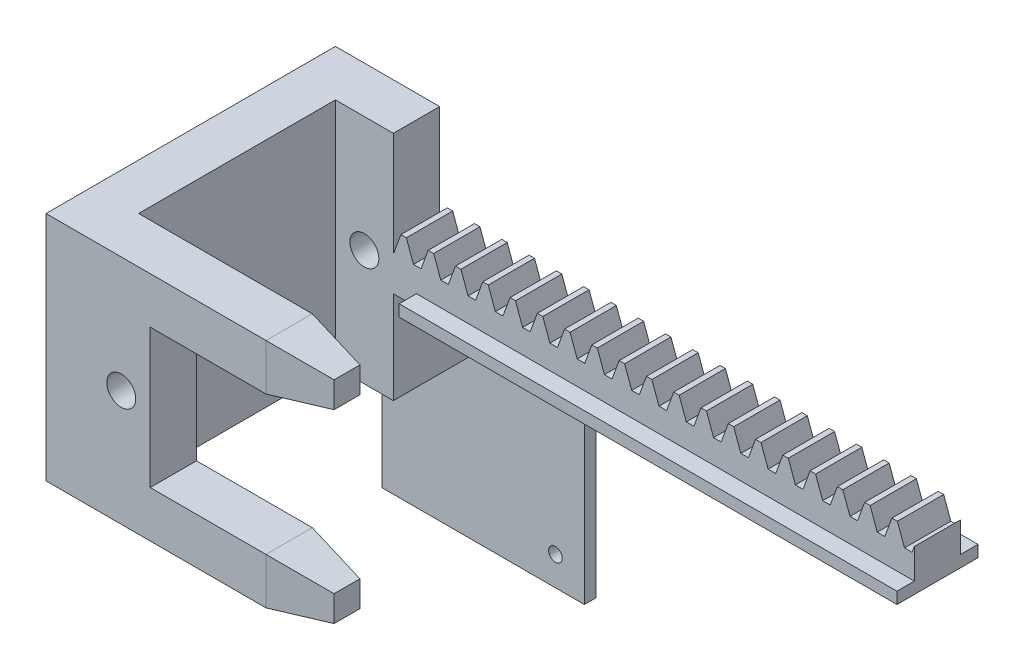
SolidWorks part; units mm, degrees
extrude "Blank" add sketch "BlankSke" against normal blind 8
sketch "BlankSke" plane through (0, 0, 0) normal (0, 0, 1) x (1, 0, 0)
  line L1 (0, 0) -> (100, 0)
  line L2 (0, 0) -> (0, 9.5)
  line L3 (0, 9.5) -> (100, 9.5)
  line L4 (100, 0) -> (100, 9.5)
  dimension "Length" = 100
  dimension "Blank_height" = 9.5
material "ABS PC"
ref_plane "Plane1" through (0, 0, 0) normal (0, 0, 1) x (1, 0, 0)
ref_plane "Plane2" through (0, 0, 0) normal (0, 1, 0) x (1, 0, 0)
ref_plane "Plane3" through (0, 0, 0) normal (1, 0, 0) x (0, 0, -1)
sketch "HoldingSke" plane through (0, 0, 0) normal (0, 1, 0) x (1, 0, 0)
  line L0 (0, 0) -> (0.0928, 0.6602)
  line L1 (-15, 0) -> (100, 0) construction
  line L2 (0, 0) -> (-2.1039, 2.3779)
  line L3 (0, 0) -> (-11.863, 4.5341)
  line L4 (0, 0) -> (7.9495, 3.3743)
  line L5 (0, 0) -> (-23.7986, -8.8762)
  line L6 (0, 0) -> (-10.5278, -7.1032)
  line L9 (-71.009, 38.7566) -> (22.9603, 72.9586)
  line L10 (-76.2, 3.8779) -> (-68.2, 3.8779)
  line L11 (0, 0) -> (-8, 0)
  line L12 (-76.2, 101.6) -> (-76.147, 101.6)
  line L13 (24.9733, 27.94) -> (52.9518, 28.4284)
  line L14 (24.9733, 27.94) -> (24.9743, 27.94)
  line L15 (24.9733, 27.94) -> (100.4006, 29.5858)
  circle A0 centre (0, 0) radius 19.05
  circle A1 centre (0, 0) radius 4
  circle A2 centre (0, 0) radius 12.7
  dimension "MPH" = 8
  dimension "Diameter" = 38.1
  dimension "Num_teeth" = 23
  dimension "Pitch" = 0.6667
  dimension "Show_teeth" = 998
  dimension "Thickness" = 12.7
  dimension "Ap" = 20
  dimension "Pitch_height" = 8
  dimension "Width" = 8
  dimension "Backlash" = 0.053
  dimension "Addendum_fac" = 1
  dimension "Dedendum_fac" = 1.25
  dimension "Clearance_fac" = 0.25
  dimension "Dedendum_add" = 0.001
  dimension "Length" = 100
  dimension "Module" = 1.5
sketch "TooCutSkeIll" plane through (0, 0, 0) normal (0, 0, 1) x (1, 0, 0)
  line L0 (-1.8687, 9.4605) -> (-0.7447, 6.3724)
  line L1 (-0.3914, 6.125) -> (0.3914, 6.125)
  line L2 (0.7447, 6.3724) -> (1.8687, 9.4605)
  line L3 (100, 9.5) -> (0, 9.5) construction
  line L4 (0, 0) -> (0, 64.897) construction
  line L5 (-13.208, 8) -> (12.954, 8) construction
  line L6 (0, 0) -> (100, 0) construction
  line L7 (1.3371, 8) -> (1.3371, 48.7463) construction
  line L8 (-1.3371, 8) -> (-1.3371, 48.7463) construction
  line L9 (1.9251, 9.5) -> (1.9251, 9.5254)
  line L10 (-1.9251, 9.5) -> (-1.9251, 9.5254)
  line L11 (-1.9251, 9.5254) -> (1.9251, 9.5254)
  arc A0 (0.3914, 6.125) -> (0.7447, 6.3724) centre (0.3914, 6.501) ccw
  arc A1 (-0.7447, 6.3724) -> (-0.3914, 6.125) centre (-0.3914, 6.501) ccw
  arc A2 (1.9251, 9.5) -> (1.8687, 9.4605) centre (1.9251, 9.44) ccw
  arc A3 (-1.8687, 9.4605) -> (-1.9251, 9.5) centre (-1.9251, 9.44) ccw
  dimension "Pitch_height" = 8
  dimension "Addendum_plus" = 1.5254
  dimension "Pressure_angle" = 20
  dimension "Gap_width" = 2.6742
  dimension "Dedendum" = 1.875
extrude "ToothCutIll" [suppressed] cut sketch "TooCutSkeIll" against normal through all
sketch "TooCutSkeSim" plane through (0, 0, 0) normal (0, 0, 1) x (1, 0, 0)
  line L0 (0.6547, 6.125) -> (-0.6547, 6.125)
  line L1 (1.8923, 9.5254) -> (0.6547, 6.125)
  line L2 (0, 17.4625) -> (0, 53.467) construction
  line L3 (1.8923, 9.5254) -> (-1.8923, 9.5254)
  line L6 (-1.8923, 9.5254) -> (-0.6547, 6.125)
  line L9 (-1.3371, 8) -> (1.3371, 8) construction
  line L10 (0, 0) -> (100, 0) construction
  line L11 (1.3371, 8) -> (1.3371, 53.467) construction
  line L12 (-1.3371, 8) -> (-1.3371, 53.467) construction
  dimension "Pitch_height" = 8
  dimension "Addendum_plus" = 1.5254
  dimension "Pressure_angle" = 20
  dimension "Gap_width" = 2.6742
  dimension "Dedendum" = 1.875
extrude "ToothCutSim" cut sketch "TooCutSkeSim" against normal through all
pattern_linear "TeethCuts" count 22 spacing 4.7124 along (1, 0, 0) of "ToothCutIll", "ToothCutSim"
sketch "Sketch1" plane through (0, 0, 0) normal (-1, 0, 0) x (0, 0, 1)
  line L0 (0, 0) -> (3, 0)
  line L1 (3, 0) -> (3, 2)
  line L2 (3, 2) -> (0, 2)
  line L3 (0, 6.125) -> (0, 0) construction
  line L4 (0, 2) -> (0, 0)
  dimension "D1" = 3
  dimension "D2" = 2
extrude "Boss-Extrude1" add sketch "Sketch1" against normal blind 100
ref_plane "Plane4" through (0, 0, -4) normal (0, 0, -1) x (-1, 0, 0)
mirror "Mirror1" about plane through (0, 0, -4) normal (0, 0, -1) of "Boss-Extrude1"
sketch "Sketch2" plane through (0, 0, 0) normal (0, -1, 0) x (-1, 0, 0)
  line L0 (0, 0) -> (-100, 0) construction
  line L1 (0, 11) -> (0, -3) construction
  line L2 (-100, 11) -> (-100, -3) construction
  line L3 (-100, -3) -> (0, -3) construction
  dimension "D1" = 3
sketch "Sketch4" plane through (0, 0, 0) normal (-1, 0, 0) x (0, 0, 1)
  line L0 (-8, -16) -> (-8, 24)
  line L1 (-8, 24) -> (42, 24)
  line L2 (42, 24) -> (42, -16)
  line L3 (42, -16) -> (-8, -16)
  line L4 (-11, 0) -> (3, 0) construction
  dimension "D1" = 40
  dimension "D2" = 50
  dimension "D3" = 24
extrude "Boss-Extrude2" add sketch "Sketch4" along normal blind 8
sketch "Sketch5" plane through (0, 0, 0) normal (1, 0, 0) x (0, 0, -1)
  line L0 (-42, 24) -> (-34, 24)
  line L1 (-42, 24) -> (8, 24) construction
  line L2 (-34, 24) -> (-34, 16)
  line L3 (-34, 16) -> (-42, 16)
  line L4 (-42, -16) -> (-42, 24) construction
  line L5 (-42, 16) -> (-42, 24)
  dimension "D1" = 8
  dimension "D2" = 8
extrude "Boss-Extrude3" add sketch "Sketch5" along normal blind 30
ref_plane "Plane5" through (0, 4, 0) normal (0, 1, 0) x (1, 0, 0)
mirror "Mirror2" about plane through (0, 4, 0) normal (0, 1, 0) of "Boss-Extrude3"
sketch "Sketch6" plane through (30, 0, 0) normal (1, 0, 0) x (0, 0, -1)
  line L0 (-42, 16) -> (-42, 24)
  line L1 (-42, 24) -> (-34, 24)
  line L2 (-34, 24) -> (-42, 24) construction
  line L3 (-34, 16) -> (-34, 24) construction
  line L4 (-34, 24) -> (-34, 16)
  line L5 (-42, 16) -> (-34, 16) construction
  line L6 (-34, 16) -> (-42, 16)
extrude "Boss-Extrude4" add sketch "Sketch6" along normal blind 10 draft 10
mirror "Mirror3" about plane through (0, 4, 0) normal (0, 1, 0) of "Boss-Extrude4"
sketch "Sketch7" plane through (0, 0, 42) normal (0, 0, 1) x (1, 0, 0)
  line L0 (0, 16) -> (10, 16)
  line L1 (30, 16) -> (0, 16) construction
  line L2 (10, 16) -> (10, -8)
  line L3 (30, -8) -> (0, -8) construction
  line L4 (10, -8) -> (0, -8)
  dimension "D1" = 10
extrude "Extrude-Thin1" add sketch "Sketch7" against normal blind 8 thin
sketch "Sketch8" plane through (0, 0, -8) normal (0, 0, -1) x (-1, 0, 0)
  line L0 (0, 24) -> (0, -16)
  line L1 (0, -16) -> (-10, -16)
  line L2 (-10, -16) -> (-10, 24)
  line L3 (-10, 24) -> (0, 24)
  dimension "D1" = 10
extrude "Boss-Extrude5" add sketch "Sketch8" against normal blind 8
sketch "Sketch9" plane through (0, 2, 0) normal (0, 1, 0) x (1, 0, 0)
  line L1 (0, -3) -> (14, -3)
  line L2 (0, -3) -> (0, 0)
  line L3 (0, 0) -> (14, 0)
  line L4 (14, -3) -> (14, 0)
  dimension "D1" = 14
  dimension "D2" = 3
extrude "Cut-Extrude1" cut sketch "Sketch9" against normal up to next
sketch "Sketch10" plane through (0, 0, 42) normal (0, 0, 1) x (1, 0, 0)
  line L0 (-8, -16) -> (30, -16) construction
  line L1 (10, 16) -> (10, -8) construction
  circle A0 centre (5, 4) radius 2.5
  dimension "D1" = 5
  dimension "D2" = 20
  dimension "D3" = 5
extrude "Cut-Extrude2" cut sketch "Sketch10" against normal through all both and the other way through all
mirror "Mirror4" about plane through (0, 0, -4) normal (0, 0, -1) of "Cut-Extrude1"
sketch "Sketch11" plane through (0, 0, -8) normal (0, 0, -1) x (-1, 0, 0)
  line L0 (-10, 0) -> (-10, -16) construction
  line L1 (8, -16) -> (-10, -16)
  line L2 (8, -16) -> (8, -11)
  line L3 (8, -11) -> (-10, -11)
  line L4 (-10, -16) -> (-10, -11)
  dimension "D1" = 5
extrude "Boss-Extrude6" add sketch "Sketch11" along normal blind 10
sketch "Sketch12" plane through (0, -16, 0) normal (0, -1, 0) x (-1, 0, 0)
  line L1 (8, 18) -> (-27, 18)
  line L2 (8, 18) -> (8, 16)
  line L3 (8, 16) -> (-27, 16)
  line L4 (-27, 18) -> (-27, 16)
  dimension "D1" = 35
  dimension "D2" = 2
extrude "Boss-Extrude7" add sketch "Sketch12" along normal blind 30
sketch "Sketch13" plane through (0, 0, -16) normal (0, 0, 1) x (1, 0, 0)
  line L0 (27, -46) -> (27, -16) construction
  line L1 (27, -46) -> (-8, -46) construction
  circle A0 centre (22, -41) radius 1.18
  dimension "D1" = 2.36
  dimension "D2" = 5
  dimension "D3" = 5
extrude "Cut-Extrude3" cut sketch "Sketch13" against normal up to next
equation "' \"Module@HoldingSke\" = 6.35"
equation "' \"Num_teeth@HoldingSke\" = 12"
equation "' \"Ap@HoldingSke\" =  20"
equation "' \"Ap@HoldingSke\" = 20"
equation "' \"Width@HoldingSke\" = 0.25 * 25.4"
equation "' \"Show_teeth@HoldingSke\" = 500"
equation "' \"Backlash@HoldingSke\" = 0.009 * 25.4"
equation "' \"Addendum_fac@HoldingSke\" = 1.0"
equation "' \"Dedendum_fac@HoldingSke\" = 1.25"
equation "' \"Dedendum_add@HoldingSke\" = 0.00005 * 25.4"
equation "' \"Clearance_fac@HoldingSke\" = 0.25"
equation "' \"Pitch_height@HoldingSke\" = 1 * 25.4"
equation "' \"Length@HoldingSke\" = 4.71 * 25.4"
equation "\"Pitch@HoldingSke\" = 1 / \"Module@HoldingSke\""
equation "\"MPH@HoldingSke\" = \"Dedendum_fac@HoldingSke\" / \"Pitch@HoldingSke\" + 2 * \"Dedendum_add@HoldingSke\" + 0.002 * 25.4"
equation "\"MPH@HoldingSke\" = ((sgn( \"MPH@HoldingSke\" - \"Pitch_height@HoldingSke\")+1)*( \"MPH@HoldingSke\" - \"Pitch_height@HoldingSke\"))/2 + \"Pitch_height@HoldingSke\""
equation "\"Blank_height@BlankSke\" = \"Pitch_height@HoldingSke\" + \"Addendum_fac@HoldingSke\"  / \"Pitch@HoldingSke\" "
equation "\"Length@BlankSke\" =  \"Length@HoldingSke\""
equation "\"Face_width@Blank\" = \"Width@HoldingSke\""
equation "\"Pressure_angle@TooCutSkeIll\" = \"Ap@HoldingSke\""
equation "\"Addendum_plus@TooCutSkeIll\" =  \"Addendum_fac@HoldingSke\"  / \"Pitch@HoldingSke\" + 0.001 *25.4"
equation "\"Dedendum@TooCutSkeIll\" = \"Dedendum_fac@HoldingSke\"  / \"Pitch@HoldingSke\""
equation "\"Pitch_height@TooCutSkeIll\" =  \"MPH@HoldingSke\""
equation "\"Gap_width@TooCutSkeIll\" = 3.14159265 / 2 / \"Pitch@HoldingSke\" + 6 * \"Backlash@HoldingSke\""
equation "\"Pressure_angle@TooCutSkeSim\" = \"Ap@HoldingSke\""
equation "\"Addendum_plus@TooCutSkeSim\" =  \"Addendum_fac@HoldingSke\"  / \"Pitch@HoldingSke\" + 0.001 * 25.4"
equation "\"Dedendum@TooCutSkeSim\" = \"Dedendum_fac@HoldingSke\"  / \"Pitch@HoldingSke\""
equation "\"Pitch_height@TooCutSkeSim\" =  \"MPH@HoldingSke\""
equation "\"Gap_width@TooCutSkeSim\" = 3.14159265 / 2 / \"Pitch@HoldingSke\" + 6 * \"Backlash@HoldingSke\""
equation "\"Root_fillet@TooCutSkeIll\" = \"Clearance_fac@HoldingSke\" / \"Pitch@HoldingSke\" + \"Dedendum_add@HoldingSke\""
equation "\"Break_rad@TooCutSkeIll\" = 0.02 / \"Pitch@HoldingSke\" * 2"
equation "\"Linear_pitch@TeethCuts\" = 3.14159265 / \"Pitch@HoldingSke\""
equation "\"Num_teeth@HoldingSke\" = int( ( \"Length@HoldingSke\" + 0 ) / (3.14159265 / \"Pitch@HoldingSke\")) + 0.9999  + 1"
equation " \"Num_teeth@TeethCuts\" = int( \"Show_teeth@HoldingSke\" ) + 1"
equation " \"Num_teeth@TeethCuts\" = ((sgn( \"Num_teeth@TeethCuts\" - \"Num_teeth@HoldingSke\" )-1)*( \"Num_teeth@TeethCuts\" - \"Num_teeth@HoldingSke\" ))/-2+ \"Num_teeth@HoldingSke\""
equation " \"Num_teeth@TeethCuts\" = ((sgn( \"Num_teeth@TeethCuts\" - 2.0)+1)*( \"Num_teeth@TeethCuts\" - 2.0))/2 +2.0"
